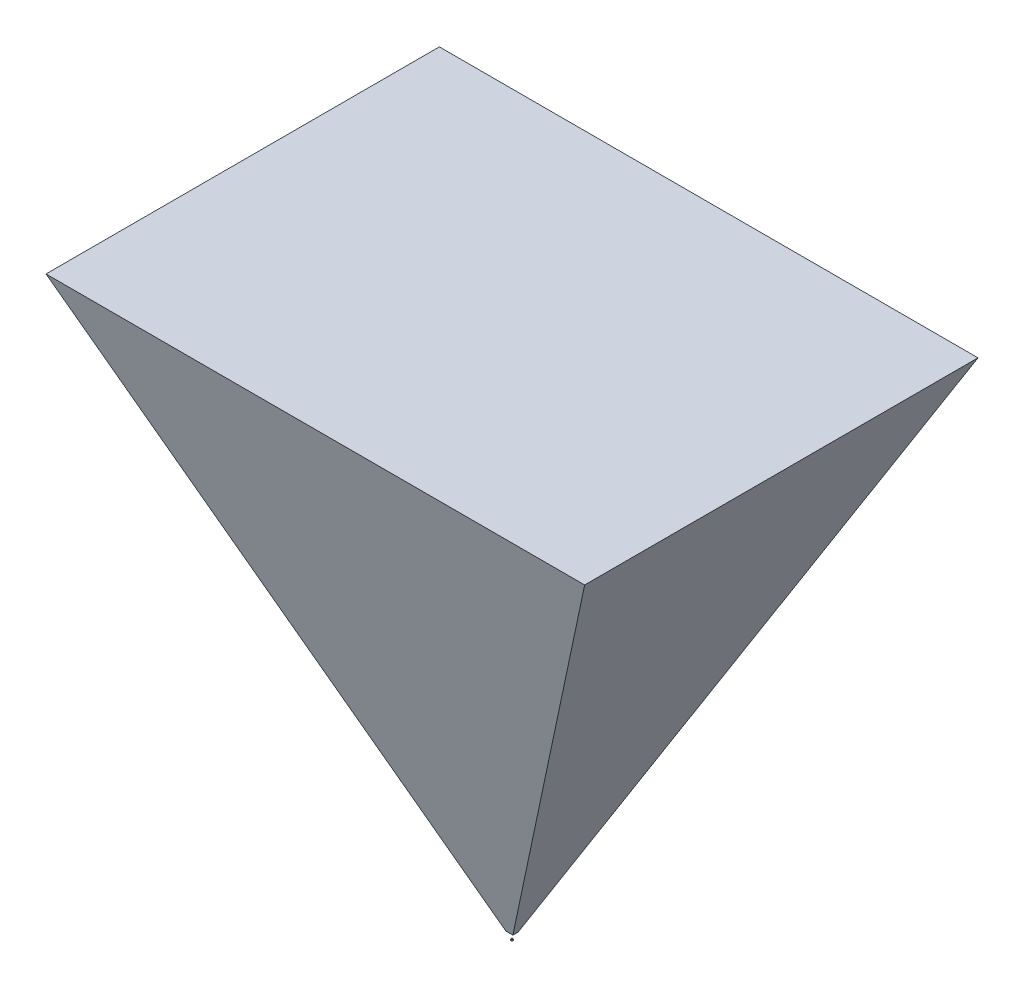
SolidWorks part; units mm, degrees
material "ABS PC"
ref_plane "Vorne" through (0, 0, 0) normal (0, 0, 1) x (1, 0, 0)
ref_plane "Oben" through (0, 0, 0) normal (0, 1, 0) x (1, 0, 0)
ref_plane "Rechts" through (0, 0, 0) normal (1, 0, 0) x (0, 0, -1)
sketch "Skizze3" plane through (0, 0, 0) normal (0, 0, 1) x (1, 0, 0)
  line L0 (0, 0) -> (0, -2.1568) construction
  line L1 (1, 0.8) -> (2.75, 0.8)
  line L2 (2.75, 0.8) -> (2.75, -2.55)
  line L3 (2.75, -2.55) -> (2.1, -2.55)
  line L4 (1, 0.8) -> (0.625, 0.425)
  line L5 (0.8125, 0.6125) -> (0.8125, 0.8) construction
  line L6 (0.8125, 0.8) -> (1, 0.8) construction
  line L7 (2.1, -2.55) -> (1.8, -2.25)
  line L8 (2.1, -2.55) -> (2.1, -2.4) construction
  line L9 (2.1, -2.4) -> (1.95, -2.4) construction
  line L10 (0, -2.55) -> (0, 0.525)
  arc A0 (1.8, -2.25) -> (0, -2.55) centre (0, 3) cw
  arc A1 (0, 0.525) -> (0.625, 0.425) centre (0, -1.4781) cw
  dimension "D6" = 0.1
  dimension "D1" = 3.35
  dimension "D2" = 5.5
  dimension "D3" = 2
  dimension "D4" = 1.25
  dimension "D5" = 3.6
  dimension "D7" = 0.8
  dimension "D8" = 0.3
revolve "Body" add sketch "Skizze3" angle 360 about L0
sketch "Skizze4" plane through (0, 0, 0) normal (0, 0, 1) x (1, 0, 0)
  line L0 (0, 0) -> (0, 1.3093) construction
  line L1 (2.75, -2.55) -> (2.75, 0.8) construction
  line L2 (2.75, -0.2) -> (3, -0.2)
  line L3 (2.75, -0.2) -> (2.75, -1.2)
  line L4 (2.75, -1.2) -> (3, -1.2)
  line L5 (3, -0.2) -> (3, -1.2)
  line L6 (2.75, 0.8) -> (-2.75, 0.8) construction
  dimension "D1" = 2
  dimension "D2" = 1
  dimension "D3" = 6
revolve "Thread" add sketch "Skizze4" angle 360 about L0
sketch "Skizze5" plane through (0, 0, 0) normal (1, 0, 0) x (0, 0, -1)
  line L0 (0, 0) -> (0, -3.7681) construction
  line L1 (2.75, 0.8) -> (2.75, 0.35)
  line L2 (2.75, -0.2) -> (2.75, 0.8) construction
  line L3 (2.75, 0.35) -> (2.3, 0.8)
  line L4 (2.75, 0.8) -> (-2.75, 0.8) construction
  line L5 (2.3, 0.8) -> (2.75, 0.8)
  dimension "D1" = 0.45
revolve "Toolface" cut sketch "Skizze5" angle 60 about L0
pattern_circular "Kreismuster1" count 3 over 360 about axis through (0, 0, 0) along (0, 1, 0) of "Toolface"
sketch "Skizze6" plane through (0, 0, 0) normal (1, 0, 0) x (0, 0, -1)
  line L0 (0, 0) -> (0, 10.2784) construction
  line L1 (-7.2794, 18.7078) -> (-553.2348, 1518.7078)
  line L2 (-553.2348, 1518.7078) -> (553.2348, 1518.7078)
  line L3 (-7.2794, 18.7078) -> (7.2794, 18.7078)
  line L4 (0, 1518.7078) -> (0, 18.7078) construction
  line L5 (-7.2794, 18.7078) -> (0, -1.2922) construction
  line L8 (7.2794, 18.7078) -> (553.2348, 1518.7078)
  point P3 (-0.625, 0.425)
  dimension "D1" = 1500
  dimension "D2" = 20
  dimension "D3" = 40
extrude "FOV - 3,6mm f/2,9" add sketch "Skizze6" along normal mid plane 3000 separate body
sketch "Skizze8" plane through (0, 0, 0) normal (0, 0, 1) x (1, 0, 0)
  line L0 (0, 0) -> (0, 233.3089) construction
  line L1 (-9.7405, 18.7078) -> (-757.6129, 1518.7078)
  line L2 (1500, 18.7078) -> (-1500, 18.7078) construction
  line L3 (1500, 1518.7078) -> (-1500, 1518.7078) construction
  line L4 (-757.6129, 1518.7078) -> (757.6129, 1518.7078)
  line L5 (-9.7405, 18.7078) -> (9.7405, 18.7078)
  line L8 (9.7405, 18.7078) -> (757.6129, 1518.7078)
  circle A0 centre (0, 0) radius 5
  point P9 (-0.625, 0.425)
  point P16 (0, 18.7078)
  point P17 (0, 1518.7078)
  dimension "D2" = 10
  dimension "D1" = 53
extrude "FOV2" cut sketch "Skizze8" against normal through all and the other way through all flip side to cut
